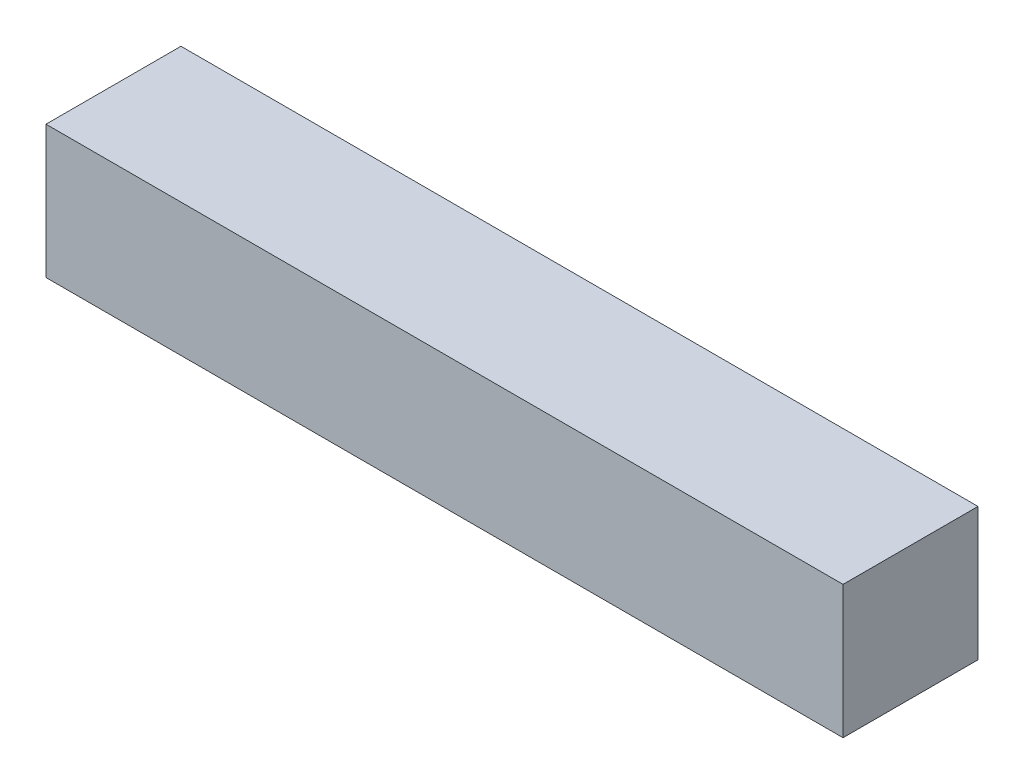
SolidWorks part; units mm, degrees
ref_plane "Front Plane" through (0, 0, 0) normal (0, 0, 1) x (1, 0, 0)
ref_plane "Top Plane" through (0, 0, 0) normal (0, 1, 0) x (1, 0, 0)
ref_plane "Right Plane" through (0, 0, 0) normal (1, 0, 0) x (0, 0, -1)
sketch "Sketch1" plane through (0, 0, 0) normal (0, 1, 0) x (1, 0, 0)
  line L1 (-75, 12.7) -> (75, 12.7)
  line L2 (-75, 12.7) -> (-75, -12.7)
  line L3 (-75, -12.7) -> (75, -12.7)
  line L4 (75, 12.7) -> (75, -12.7)
  line L5 (-75, 12.7) -> (75, -12.7) construction
  line L6 (-75, -12.7) -> (75, 12.7) construction
  point P0 (0, 0)
  dimension "D1" = 150
  dimension "D2" = 25.4
extrude "Boss-Extrude1" add sketch "Sketch1" along normal blind 25
